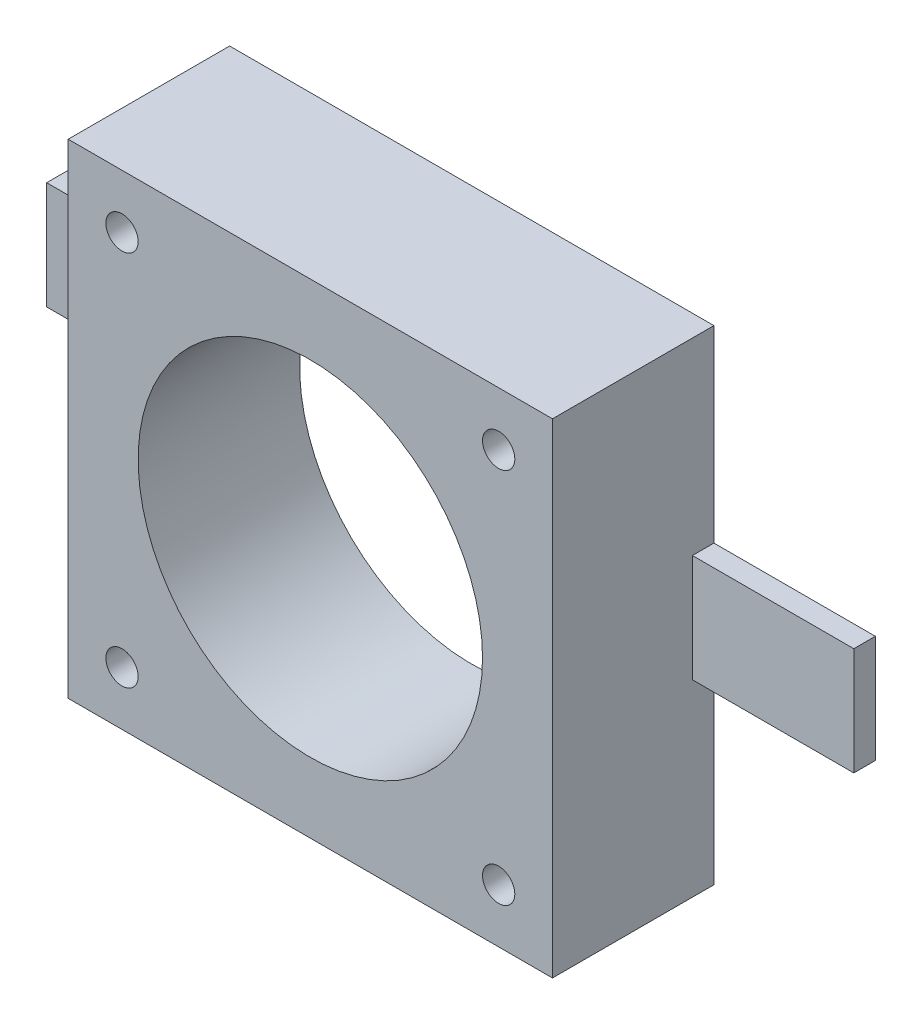
SolidWorks part; units mm, degrees
ref_plane "Alzado" through (0, 0, 0) normal (0, 0, 1) x (1, 0, 0)
ref_plane "Planta" through (0, 0, 0) normal (0, 1, 0) x (1, 0, 0)
ref_plane "Vista lateral" through (0, 0, 0) normal (1, 0, 0) x (0, 0, -1)
sketch "Croquis1" plane through (0, 0, 0) normal (0, 0, 1) x (1, 0, 0)
  line L1 (-22.5, -22.5) -> (22.5, -22.5)
  line L2 (-22.5, -22.5) -> (-22.5, 22.5)
  line L3 (-22.5, 22.5) -> (22.5, 22.5)
  line L4 (22.5, -22.5) -> (22.5, 22.5)
  line L5 (-22.5, -22.5) -> (22.5, 22.5) construction
  line L6 (-22.5, 22.5) -> (22.5, -22.5) construction
  circle A0 centre (0, 0) radius 16
extrude "Saliente-Extruir1" add sketch "Croquis1" along normal blind 15
sketch "Croquis2" plane through (0, 0, 15) normal (0, 0, 1) x (1, 0, 0)
  line L0 (-22.5, 22.5) -> (-17.5, 22.5) construction
  line L1 (22.5, 22.5) -> (-22.5, 22.5) construction
  line L2 (-17.5, 22.5) -> (-17.5, 17.5) construction
  line L3 (22.5, -22.5) -> (22.5, -17.5) construction
  line L4 (22.5, -22.5) -> (22.5, 22.5) construction
  line L5 (22.5, -17.5) -> (17.5, -17.5) construction
  line L6 (-17.5, -22.5) -> (-17.5, -17.5) construction
  line L7 (-22.5, -22.5) -> (22.5, -22.5) construction
  line L8 (17.5, 22.5) -> (17.5, 17.5) construction
  circle A0 centre (-17.5, 17.5) radius 1.5
  circle A1 centre (17.5, -17.5) radius 1.5
  circle A2 centre (-17.5, -17.5) radius 1.5
  circle A3 centre (17.5, 17.5) radius 1.5
extrude "Cortar-Extruir1" cut sketch "Croquis2" against normal blind 15
sketch "Croquis3" plane through (22.5, 0, 0) normal (1, 0, 0) x (0, 0, -1)
  line L0 (0, 0) -> (-2, 0) construction
  line L1 (0, -22.5) -> (0, 22.5) construction
  line L2 (-2, 0) -> (-2, 5)
  line L3 (-2, 0) -> (-2, -5)
  line L4 (-2, -5) -> (0, -5)
  line L5 (0, -5) -> (0, 5)
  line L6 (0, 5) -> (-2, 5)
extrude "Saliente-Extruir2" add sketch "Croquis3" along normal blind 15
mirror "Simetría1" about plane through (0, 0, 0) normal (1, 0, 0) of "Saliente-Extruir2"
